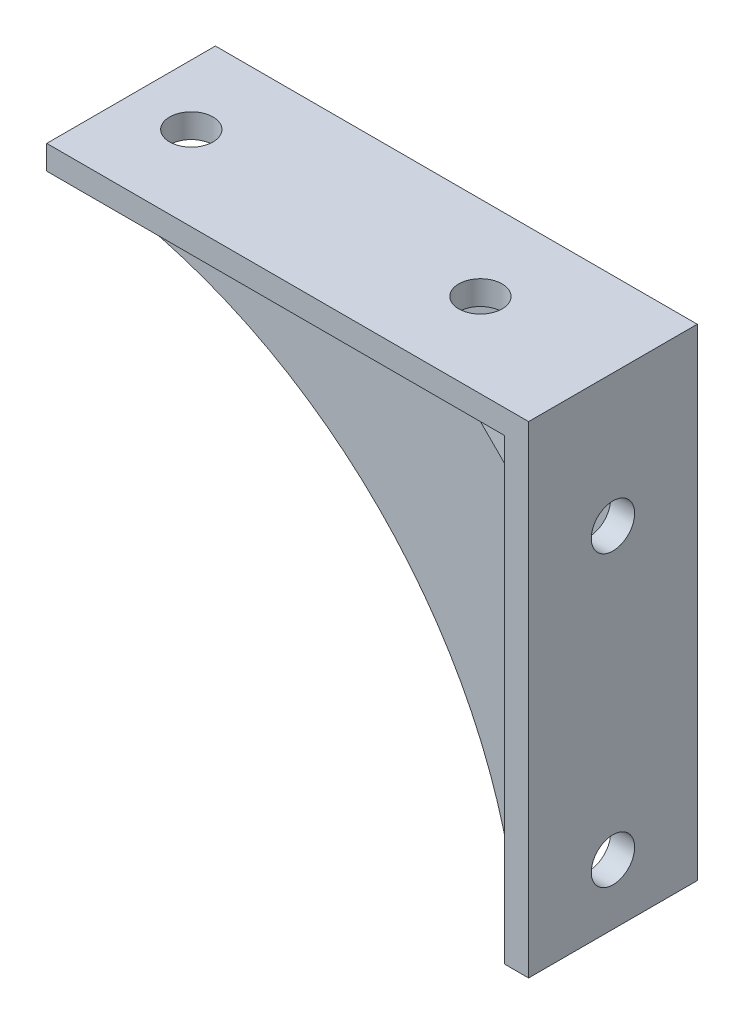
SolidWorks part; units mm, degrees
material "Plain Carbon Steel"
ref_plane "Front Plane" through (0, 0, 0) normal (0, 0, 1) x (1, 0, 0)
ref_plane "Top Plane" through (0, 0, 0) normal (0, 1, 0) x (1, 0, 0)
ref_plane "Right Plane" through (0, 0, 0) normal (1, 0, 0) x (0, 0, -1)
sketch "Sketch2" plane through (0, 0, 0) normal (0, 0, 1) x (1, 0, 0)
  line L0 (-200, 0) -> (0, 0)
  line L1 (0, 0) -> (0, -200)
  dimension "D1" = 200
extrude "Extrude-Thin1" add sketch "Sketch2" along normal mid plane 70 thin
ref_plane "Plane1" through (0, 0, -30) normal (0, 0, -1) x (-1, 0, 0)
sketch "Sketch3" plane through (0, 0, -30) normal (0, 0, -1) x (-1, 0, 0)
  line L0 (30, -10) -> (10, -30)
  line L1 (200, -10) -> (10, -10) construction
  line L2 (10, -10) -> (10, -200) construction
  line L3 (10, -30) -> (10, -185)
  line L5 (185, -10) -> (30, -10)
  line L6 (200, -10) -> (200, 0) construction
  arc A0 (10, -185) -> (185, -10) centre (208.6024, -208.6024) cw
  dimension "D4" = 200
  dimension "D1" = 15
  dimension "D2" = 20
  dimension "D3" = 45
extrude "Boss-Extrude2" add sketch "Sketch3" against normal blind 10
mirror "Mirror1" about plane through (0, 0, 0) normal (0, 0, 1) of "Boss-Extrude2"
sketch "Sketch4" plane through (-10, 0, 0) normal (-1, 0, 0) x (0, 0, 1)
  line L0 (35, -200) -> (-35, -200) construction
  circle A0 centre (0, -55) radius 9
  circle A1 centre (0, -175) radius 9
  dimension "D1" = 18
  dimension "D2" = 25
  dimension "D3" = 120
extrude "Cut-Extrude1" cut sketch "Sketch4" against normal through all
pattern_circular "CirPattern1" count 4 over 360 about axis through (0, 0, 35) along (0, 0, -1) of "Cut-Extrude1"
